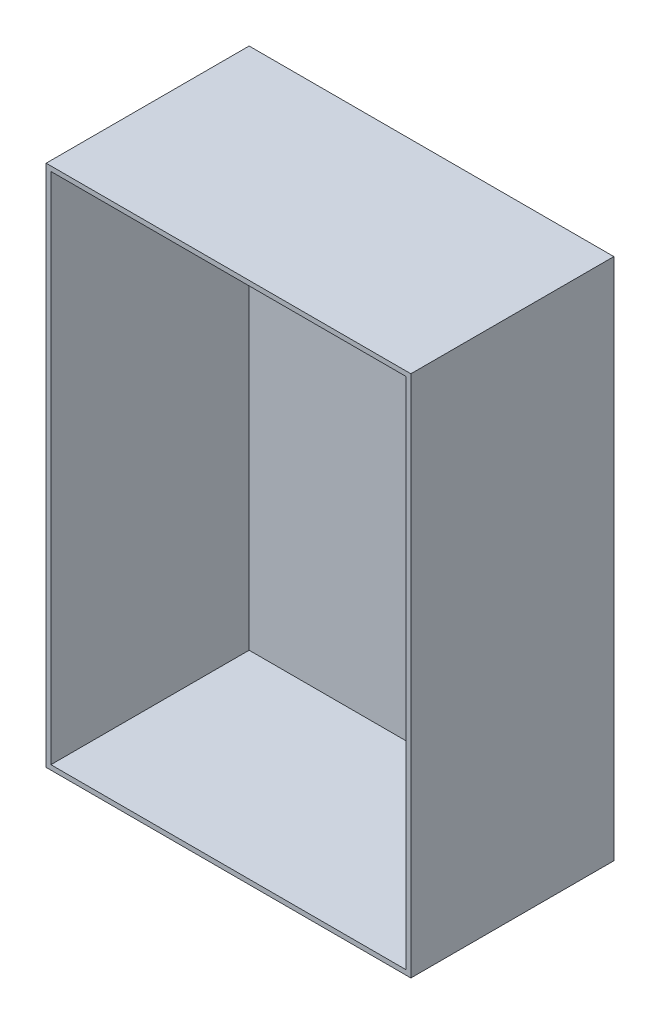
SolidWorks part; units mm, degrees
ref_plane "Front Plane" through (0, 0, 0) normal (0, 0, 1) x (1, 0, 0)
ref_plane "Top Plane" through (0, 0, 0) normal (0, 1, 0) x (1, 0, 0)
ref_plane "Right Plane" through (0, 0, 0) normal (1, 0, 0) x (0, 0, -1)
sketch "Sketch1" plane through (0, 0, 0) normal (0, 0, 1) x (1, 0, 0)
  line L1 (0, 0) -> (230, 0)
  line L2 (0, 0) -> (0, 330)
  line L3 (0, 330) -> (230, 330)
  line L4 (230, 0) -> (230, 330)
  line L5 (3, 3) -> (227, 3)
  line L6 (3, 3) -> (3, 327)
  line L7 (3, 327) -> (227, 327)
  line L8 (227, 3) -> (227, 327)
  dimension "D1" = 3
  dimension "D2" = 227
  dimension "D3" = 230
  dimension "D4" = 3
  dimension "D5" = 327
  dimension "D6" = 330
extrude "Profile" add sketch "Sketch1" along normal blind 128
sketch "Sketch2" plane through (0, 0, 0) normal (0, 0, 1) x (1, 0, 0)
  line L1 (3, 3) -> (227, 3)
  line L2 (3, 3) -> (3, 327)
  line L3 (3, 327) -> (227, 327)
  line L4 (227, 3) -> (227, 327)
extrude "Back" add sketch "Sketch2" along normal blind 3
equation "\"Profile_Depth\" = 128mm"
equation "\"D1@Profile\" = \"Profile_Depth\""
equation "\"Profile_Sketch_1\" = 3mm"
equation "\"D1@Sketch1\" = \"Profile_Sketch_1\""
equation "\"Profile_Sketch_2\" = 227mm"
equation "\"D2@Sketch1\" = \"Profile_Sketch_2\""
equation "\"Profile_Sketch_3\" = 230mm"
equation "\"D3@Sketch1\" = \"Profile_Sketch_3\""
equation "\"Profile_Sketch_4\" = 3mm"
equation "\"D4@Sketch1\" = \"Profile_Sketch_4\""
equation "\"Profile_Sketch_5\" = 327mm"
equation "\"D5@Sketch1\" = \"Profile_Sketch_5\""
equation "\"Profile_Sketch_6\" = 330mm"
equation "\"D6@Sketch1\" = \"Profile_Sketch_6\""
equation "\"Back_Depth\" = 3mm"
equation "\"D1@Back\" = \"Back_Depth\""
equation "\"EnvelopeWidth\" = 230mm"
equation "\"EnvelopeHeight\" = 330mm"
